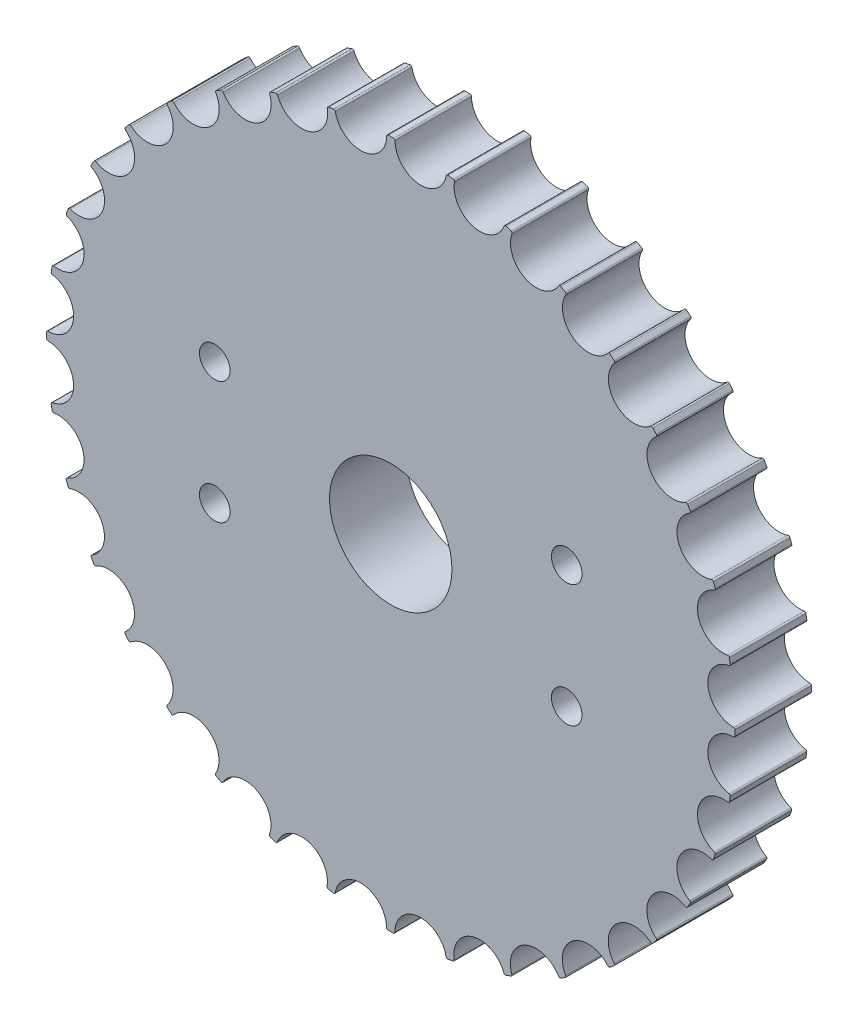
SolidWorks part; units mm, degrees
ref_plane "정면" through (0, 0, 0) normal (0, 0, 1) x (1, 0, 0)
ref_plane "윗면" through (0, 0, 0) normal (0, 1, 0) x (1, 0, 0)
ref_plane "우측면" through (0, 0, 0) normal (1, 0, 0) x (0, 0, -1)
sketch "스케치1" plane through (0, 0, 0) normal (0, 0, 1) x (1, 0, 0)
  circle A0 centre (0, 0) radius 45
  dimension "D1" = 90
extrude "보스-돌출1" add sketch "스케치1" along normal blind 10
sketch "스케치2" plane through (0, 0, 10) normal (0, 0, 1) x (1, 0, 0)
  line L0 (0, 0) -> (0, 53.4651) construction
  line L1 (0, 0) -> (9.1386, 52.0133) construction
  line L2 (0, 0) -> (-9.7027, 52.5525) construction
  circle A0 centre (3.9357, 44.8276) radius 3.38
  circle A2 centre (0, 0) radius 45 construction
  circle A6 centre (11.6601, 43.4631) radius 3.38
  circle A7 centre (19.0303, 40.778) radius 3.38
  circle A8 centre (25.8222, 36.854) radius 3.38
  circle A9 centre (31.8295, 31.8101) radius 3.38
  circle A10 centre (36.8697, 25.7997) radius 3.38
  circle A11 centre (40.7897, 19.0054) radius 3.38
  circle A12 centre (43.4702, 11.6336) radius 3.38
  circle A13 centre (44.83, 3.9083) radius 3.38
  circle A14 centre (44.8276, -3.9357) radius 3.38
  circle A15 centre (43.4631, -11.6601) radius 3.38
  circle A16 centre (40.778, -19.0303) radius 3.38
  circle A17 centre (36.854, -25.8222) radius 3.38
  circle A18 centre (31.8101, -31.8295) radius 3.38
  circle A19 centre (25.7997, -36.8697) radius 3.38
  circle A20 centre (19.0054, -40.7897) radius 3.38
  circle A21 centre (11.6336, -43.4702) radius 3.38
  circle A22 centre (3.9083, -44.83) radius 3.38
  circle A23 centre (-3.9357, -44.8276) radius 3.38
  circle A24 centre (-11.6601, -43.4631) radius 3.38
  circle A25 centre (-19.0303, -40.778) radius 3.38
  circle A26 centre (-25.8222, -36.854) radius 3.38
  circle A27 centre (-31.8295, -31.8101) radius 3.38
  circle A28 centre (-36.8697, -25.7997) radius 3.38
  circle A29 centre (-40.7897, -19.0054) radius 3.38
  circle A30 centre (-43.4702, -11.6336) radius 3.38
  circle A31 centre (-44.83, -3.9083) radius 3.38
  circle A32 centre (-44.8276, 3.9357) radius 3.38
  circle A33 centre (-43.4631, 11.6601) radius 3.38
  circle A34 centre (-40.778, 19.0303) radius 3.38
  circle A35 centre (-36.854, 25.8222) radius 3.38
  circle A36 centre (-31.8101, 31.8295) radius 3.38
  circle A37 centre (-25.7997, 36.8697) radius 3.38
  circle A38 centre (-19.0054, 40.7897) radius 3.38
  circle A39 centre (-11.6336, 43.4702) radius 3.38
  circle A40 centre (-3.9083, 44.83) radius 3.38
  dimension "D1" = 106.9058
  dimension "D2" = 36
extrude "컷-돌출2" cut sketch "스케치2" against normal blind 50
fillet "필렛1" radius 0.2 72 edges at (44.9965, -0.5599, 5) (44.4057, -7.2893, 5) (44.4101, 7.2621, 5) (44.9969, 0.5324, 5) (42.4744, 14.8635, 5) (44.2208, 8.338, 5) (39.2481, 22.0133, 5) (42.1011, 15.8901, 5) (34.8293, 28.4943, 5) (38.7022, 22.9595, 5) (29.3521, 34.1094, 5) (34.1273, 29.3313, 5) (22.9832, 38.6882, 5) (28.5156, 34.8118, 5) (15.9159, 42.0914, 5) (22.0373, 39.2346, 5) (44.2157, -8.365, 5) (42.4653, -14.8895, 5) (42.0914, -15.9159, 5) (39.2346, -22.0373, 5) (38.6882, -22.9832, 5) (34.8118, -28.5156, 5) (34.1094, -29.3521, 5) (29.3313, -34.1273, 5) (28.4943, -34.8293, 5) (22.9595, -38.7022, 5) (22.0133, -39.2481, 5) (15.8901, -42.1011, 5) (14.8635, -42.4744, 5) (8.338, -44.2208, 5) (7.2621, -44.4101, 5) (0.5324, -44.9969, 5) (-0.5599, -44.9965, 5) (-7.2893, -44.4057, 5) (-8.365, -44.2157, 5) (-14.8895, -42.4653, 5) (-15.9159, -42.0914, 5) (-22.0373, -39.2346, 5) (-22.9832, -38.6882, 5) (-28.5156, -34.8118, 5) (-29.3521, -34.1094, 5) (-34.1273, -29.3313, 5) (-34.8293, -28.4943, 5) (-38.7022, -22.9595, 5) (-39.2481, -22.0133, 5) (-42.1011, -15.8901, 5) (-42.4744, -14.8635, 5) (-44.2208, -8.338, 5) (-44.4101, -7.2621, 5) (-44.9969, -0.5324, 5) (-44.9965, 0.5599, 5) (-44.4057, 7.2893, 5) (-44.2157, 8.365, 5) (-42.4653, 14.8895, 5) (-42.0914, 15.9159, 5) (-39.2346, 22.0373, 5) (-38.6882, 22.9832, 5) (-34.8118, 28.5156, 5) (-34.1094, 29.3521, 5) (-29.3313, 34.1273, 5) (-28.4943, 34.8293, 5) (-22.9595, 38.7022, 5) (-22.0133, 39.2481, 5) (-15.8901, 42.1011, 5) (-14.8635, 42.4744, 5) (-8.338, 44.2208, 5) (-7.2621, 44.4101, 5) (-0.5324, 44.9969, 5) (0.5599, 44.9965, 5) (7.2893, 44.4057, 5) (8.365, 44.2157, 5) (14.8895, 42.4653, 5)
sketch "스케치4" plane through (0, 0, 10) normal (0, 0, 1) x (1, 0, 0)
  circle A0 centre (0, 0) radius 8
  dimension "D1" = 16
extrude "컷-돌출3" cut sketch "스케치4" against normal blind 10
sketch "스케치5" plane through (0, 0, 10) normal (0, 0, 1) x (1, 0, 0)
  line L0 (-52.1074, 0) -> (52.2141, 0) construction
  line L1 (-52.1074, -15) -> (52.2141, -15)
  line L2 (-52.1074, 15) -> (52.2141, 15)
  line L3 (0, 53.1222) -> (0, -55.2945) construction
  line L4 (-30, 53.1222) -> (-30, -55.2945)
  line L5 (30, 53.1222) -> (30, -55.2945)
  circle A0 centre (-23, 8) radius 2
  circle A1 centre (23, 8) radius 2
  circle A2 centre (23, -8) radius 2
  circle A3 centre (-23, -8) radius 2
  dimension "D5" = 4
  dimension "D7" = 7
  dimension "D6" = 7
  dimension "D1" = 15
  dimension "D2" = 15
  dimension "D3" = 30
  dimension "D4" = 30
extrude "컷-돌출4" cut sketch "스케치5" against normal blind 10 contours A3 | A0 | A1 | A2
